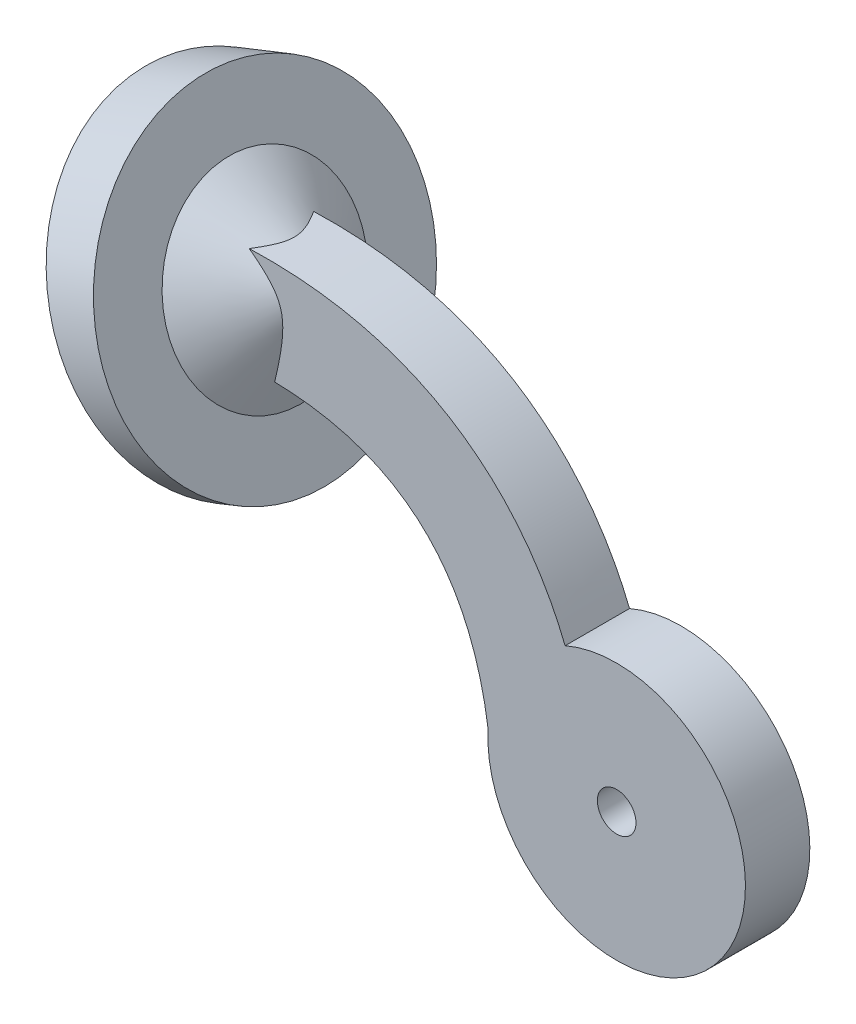
SolidWorks part; units mm, degrees
ref_plane "Front Plane" through (0, 0, 0) normal (0, 0, 1) x (1, 0, 0)
ref_plane "Top Plane" through (0, 0, 0) normal (0, 1, 0) x (1, 0, 0)
ref_plane "Right Plane" through (0, 0, 0) normal (1, 0, 0) x (0, 0, -1)
sketch "Sketch1" plane through (0, 0, 0) normal (0, 0, 1) x (1, 0, 0)
  circle A0 centre (0, 0) radius 10
  circle A1 centre (0, 0) radius 10 construction
extrude "Boss-Extrude1" add sketch "Sketch1" along normal blind 5
sketch "Sketch2" plane through (0, 0, 0) normal (0, 0, -1) x (-1, 0, 0)
  line L0 (28.2267, 15.6114) -> (31.3879, 23.607)
  line L1 (31.3879, 23.607) -> (28.4927, 23.607)
  line L2 (1.7023, -2.0399) -> (9.6909, -2.4673)
  circle A0 centre (0, 0) radius 10 construction
  spline S0 degree 2 poles (9.6909, -2.4673) (10.6892, 16.1948) (28.2267, 15.6114) knots 0 0 0 1 1 1
  spline S1 degree 1 poles (1.7023, -2.0399) (28.4927, 23.607) knots 0 0 1 1 construction
  spline S2 degree 3 poles (1.7023, -2.0399) (1.7515, -1.1196) (1.9056, 0.7363) (2.44, 4.2792) (3.5736, 8.5076) (5.8262, 13.1819) (9.086, 17.2628) (13.2591, 20.4298) (18.0301, 22.5007) (22.2801, 23.3711) (25.7843, 23.6367) (27.5953, 23.6368) (28.4927, 23.607) knots 0 0 0 0 0.0625 0.125 0.25 0.375 0.5 0.625 0.75 0.875 0.9375 1 1 1 1
  dimension "D1" = 8
extrude "Boss-Extrude2" add sketch "Sketch2" against normal blind 5
sketch "Sketch3" plane through (-19.0732, -7.5408, 0) normal (-0.93, -0.3677, 0) x (0, 0, 1)
  line L0 (5, 24.896) -> (5, 33.4938) construction
  line L2 (5, 24.896) -> (0, 24.896) construction
  circle A0 centre (2.5, 29.1949) radius 12.5
  point P9 (5, 29.1949)
  point P10 (2.5, 24.896)
  dimension "D1" = 25
extrude "Boss-Extrude3" add sketch "Sketch3" along normal blind 5
ref_plane "Plane1" through (0, 0, 15) normal (0, 0, 1) x (1, 0, 0)
sketch "Sketch5" plane through (-19.0732, -7.5408, 0) normal (0.93, 0.3677, 0) x (0, 0, -1)
  circle A2 centre (-2.5, 29.1949) radius 7.5
  dimension "D1" = 15
extrude "Boss-Extrude4" add sketch "Sketch5" along normal blind 5 draft 52
sketch "Sketch11" plane through (0, 0, 15) normal (0, 0, 1) x (1, 0, 0)
  line L0 (-39.0529, 29.3953) -> (-26.6285, 7.4245)
  line L1 (-29.8612, 6.1464) -> (-25.2114, 7.9847) construction
  line L2 (-26.6285, 7.4245) -> (-33.6203, 1.8655)
  line L3 (-33.6203, 1.8655) -> (-39.0529, 29.3953)
extrude "Cut-Extrude4" cut sketch "Sketch11" against normal blind 26
sketch "Sketch12" plane through (0, 0, 0) normal (0, 0, -1) x (-1, 0, 0)
  circle A0 centre (0, 0) radius 1.5 construction
  circle A1 centre (0, 0) radius 1.5
extrude "Cut-Extrude5" cut sketch "Sketch12" against normal blind 10
